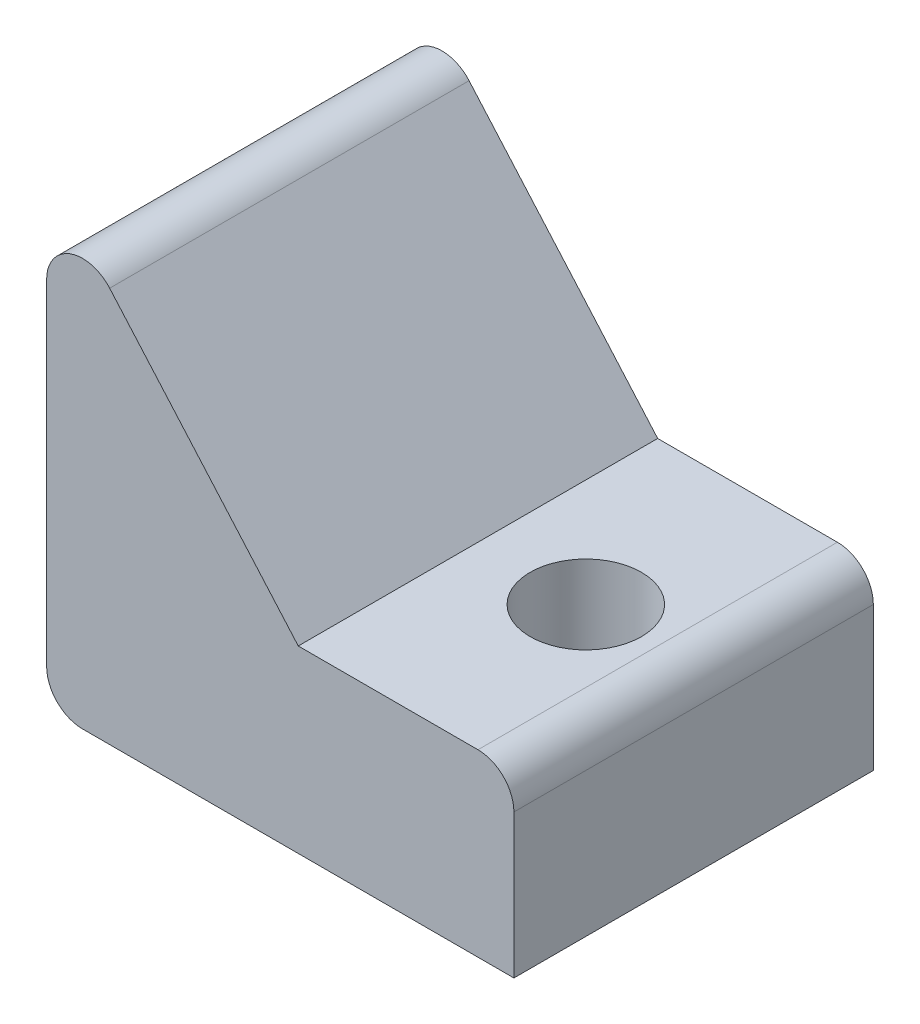
SolidWorks part; units mm, degrees
ref_plane "Front" through (0, 0, 0) normal (0, 0, 1) x (1, 0, 0)
ref_plane "Top" through (0, 0, 0) normal (0, 1, 0) x (1, 0, 0)
ref_plane "Right" through (0, 0, 0) normal (1, 0, 0) x (0, 0, -1)
sketch "Sketch1" plane through (0, 0, 0) normal (0, 0, 1) x (1, 0, 0)
  line L0 (1, 0) -> (13, 0)
  line L1 (13, 0) -> (13, 4)
  line L2 (12, 5) -> (7, 5)
  line L3 (0, 1) -> (0, 10.3386)
  line L4 (1.7526, 10.9971) -> (7, 5)
  arc A1 (0, 10.3386) -> (1.7526, 10.9971) centre (1, 10.3386) cw
  arc A2 (13, 4) -> (12, 5) centre (12, 4) ccw
  arc A3 (1, 0) -> (0, 1) centre (1, 1) cw
  point P8 (0, 13)
  point P11 (13, 5)
  point P14 (0, 0)
  dimension "D1" = 5
  dimension "D2" = 13
  dimension "D3" = 1
  dimension "D4" = 1
  dimension "D5" = 6
  dimension "D6" = 13
extrude "Boss-Extrude1" add sketch "Sketch1" along normal mid plane 10
sketch "Sketch2" plane through (0, 0, 0) normal (0, -1, 0) x (1, 0, 0)
  line L0 (12.2825, 0) -> (-1.8618, 0) construction
  line L1 (13, 5) -> (13, -5) construction
  circle A0 centre (10, 0) radius 1.55
  dimension "D1" = 3
  dimension "D2" = 3.1
extrude "Cut-Extrude1" cut sketch "Sketch2" against normal blind 10
